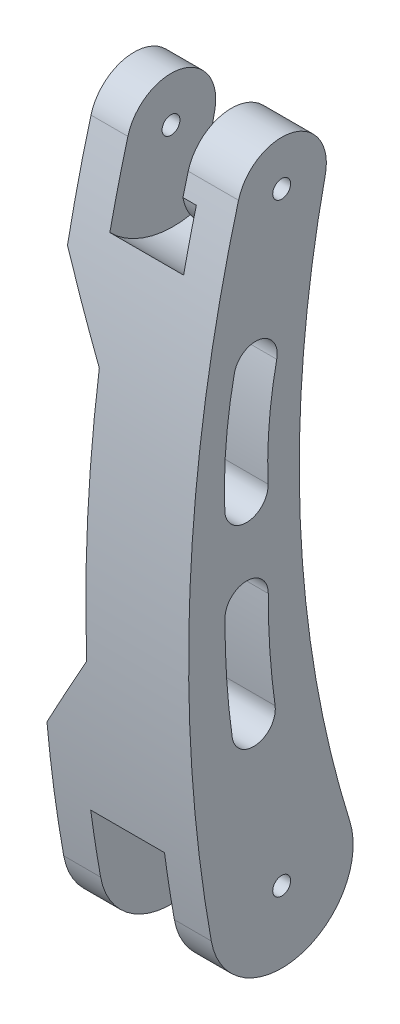
SolidWorks part; units mm, degrees
ref_plane "Plan de face" through (0, 0, 0) normal (0, 0, 1) x (1, 0, 0)
ref_plane "Plan de dessus" through (0, 0, 0) normal (0, 1, 0) x (1, 0, 0)
ref_plane "Plan de droite" through (0, 0, 0) normal (1, 0, 0) x (0, 0, -1)
sketch "Sketch1" plane through (0, 0, 0) normal (1, 0, 0) x (0, 0, -1)
  line L0 (0, 0) -> (0, 31.8922) construction
  line L1 (5.0656, 55.484) -> (-20.7338, 60.769) construction
  line L2 (7.6328, 36.3738) -> (-20.1612, 33.5121) construction
  line L3 (3.9429, 77.8355) -> (-19.7041, 80.4177) construction
  line L4 (4.9513, 101.6614) -> (-16.6278, 105.4128) construction
  arc A0 (-15.7469, -2.8345) -> (15.2745, 4.7632) centre (0, 0) ccw
  arc A1 (9.7669, 132.8534) -> (-9.6513, 137.6176) centre (0, 135) ccw
  circle A2 centre (0, 135) radius 2
  circle A3 centre (0, 0) radius 2
  arc A4 (-15.7469, -2.8345) -> (-9.6513, 137.6176) centre (299.1915, 53.8556) cw
  arc A5 (9.7669, 132.8534) -> (15.2745, 4.7632) centre (253.9392, 79.1889) ccw
  arc A6 (-7.8341, 58.1265) -> (-6.2642, 34.943) centre (152.3595, 57.3292) ccw construction
  arc A11 (-7.8341, 58.1265) -> (-6.2642, 34.943) centre (152.3595, 57.3292) ccw construction
  arc A12 (-12.6754, 58.1506) -> (-11.0581, 34.2664) centre (152.3595, 57.3292) ccw
  arc A13 (-2.9928, 58.1024) -> (-1.4703, 35.6195) centre (152.3595, 57.3292) ccw
  arc A14 (-2.9928, 58.1024) -> (-12.6754, 58.1506) centre (-7.8341, 58.1265) ccw
  arc A15 (-11.0581, 34.2664) -> (-1.4703, 35.6195) centre (-6.2642, 34.943) ccw
  arc A16 (-5.8383, 103.5371) -> (-7.8806, 79.1266) centre (152.311, 78.0144) ccw construction
  arc A17 (-5.8383, 103.5371) -> (-7.8806, 79.1266) centre (90.3799, 83.196) ccw construction
  arc A18 (-10.5749, 104.5385) -> (-12.7179, 78.9263) centre (90.3799, 83.196) ccw
  arc A19 (-1.1016, 102.5357) -> (-3.0434, 79.3269) centre (90.3799, 83.196) ccw
  arc A20 (-1.1016, 102.5357) -> (-10.5749, 104.5385) centre (-5.8383, 103.5371) ccw
  arc A21 (-12.7179, 78.9263) -> (-3.0434, 79.3269) centre (-7.8806, 79.1266) ccw
  point P19 (-7.4701, 46.5062)
  point P33 (-7.6224, 91.3957)
  dimension "D4" = 20
  dimension "D5" = 320
  dimension "D6" = 250
  dimension "D1" = 16
  dimension "D2" = 135
  dimension "D3" = 32
  dimension "D7" = 35.5
extrude "Boss-Extrude1" add sketch "Sketch1" along normal blind 33
ref_plane "Plane1" through (8.25, 0, 0) normal (-1, 0, 0) x (0, 0, 1)
sketch "Sketch2" plane through (8.25, 0, 0) normal (-1, 0, 0) x (0, 0, 1)
  line L3 (0, 135) -> (0, 128.3969) construction
  arc A0 (9.6513, 137.6176) -> (-9.7669, 132.8534) centre (0, 135) ccw construction
  arc A1 (9.6513, 137.6176) -> (-9.7669, 132.8534) centre (0, 135) ccw
  arc A2 (15.7469, -2.8345) -> (9.6513, 137.6176) centre (-299.1915, 53.8556) ccw construction
  arc A3 (-15.2745, 4.7632) -> (-9.7669, 132.8534) centre (-253.9392, 79.1889) ccw construction
  arc A4 (13.6848, 121.0001) -> (9.6513, 137.6176) centre (-299.1915, 53.8556) ccw
  arc A5 (-6.6696, 116.0363) -> (-9.7669, 132.8534) centre (-253.9392, 79.1889) ccw
  arc A6 (13.6848, 121.0001) -> (-6.6696, 116.0363) centre (-0.5289, 135.0702) cw
  dimension "D3" = 20
  dimension "D1" = 17.1
  dimension "D2" = 17.1
extrude "Cut-Extrude1" cut sketch "Sketch2" against normal blind 13.5
sketch "Sketch3" plane through (8.25, 0, 0) normal (-1, 0, 0) x (0, 0, 1)
  line L0 (-3.8062, -15.5407) -> (4.8189, 21.4675) construction
  arc A0 (15.7469, -2.8345) -> (9.6513, 137.6176) centre (-299.1915, 53.8556) ccw construction
  arc A1 (-15.2745, 4.7632) -> (-9.7669, 132.8534) centre (-253.9392, 79.1889) ccw construction
  arc A2 (-15.2745, 4.7632) -> (15.7469, -2.8345) centre (0, 0) ccw construction
  arc A3 (15.7469, -2.8345) -> (17.9617, 11.2666) centre (-299.1915, 53.8556) ccw
  arc A4 (-15.2745, 4.7632) -> (-11.4934, 18.1967) centre (-253.9392, 79.1889) ccw
  arc A5 (-15.2745, 4.7632) -> (15.7469, -2.8345) centre (0, 0) ccw
  arc A6 (-11.4934, 18.1967) -> (17.9617, 11.2666) centre (0.2385, 1.9991) cw
  dimension "D1" = 20
  dimension "D2" = 38
extrude "Cut-Extrude2" cut sketch "Sketch3" against normal blind 16.5
sketch "Sketch4" plane through (0, 0, 0) normal (-1, 0, 0) x (0, 0, 1)
  line L0 (5.5085, 3.4197) -> (6.2141, 16.8837)
  line L1 (1.1904, 17.9515) -> (-3.6413, 5.3646)
  circle A0 centre (0, 0) radius 2
  arc A1 (6.2141, 16.8837) -> (1.1904, 17.9515) centre (3.6177, 17.0198) ccw
  arc A2 (-3.8104, 5.1421) -> (-3.6413, 5.3646) centre (-4.1081, 5.5438) ccw
  arc A3 (-3.8104, 5.1421) -> (5.5725, 3.1477) centre (0, 0) ccw
  arc A4 (5.5085, 3.4197) -> (5.5725, 3.1477) centre (6.0078, 3.3936) ccw
extrude "Cut-Extrude3" cut sketch "Sketch4" against normal blind 5
sketch "Sketch6" plane through (21.75, 0, 0) normal (-1, 0, 0) x (0, 0, 1)
  circle A0 centre (0, 135) radius 2 construction
  arc A1 (-6.6696, 116.0363) -> (13.6848, 121.0001) centre (-0.5289, 135.0702) ccw construction
  arc A2 (-6.6696, 116.0363) -> (-9.7669, 132.8534) centre (-253.9392, 79.1889) ccw construction
  arc A3 (13.6848, 121.0001) -> (9.6513, 137.6176) centre (-299.1915, 53.8556) ccw construction
  arc A4 (-6.6696, 116.0363) -> (-8.8418, 128.4561) centre (-253.9392, 79.1889) ccw
  arc A5 (13.6848, 121.0001) -> (10.8373, 133.1152) centre (-299.1915, 53.8556) ccw
  arc A6 (-8.8418, 128.4561) -> (10.8373, 133.1152) centre (0, 135) ccw
  arc A7 (15.7469, -2.8345) -> (9.6513, 137.6176) centre (-299.1915, 53.8556) ccw construction
  arc A8 (-6.6696, 116.0363) -> (13.6848, 121.0001) centre (-0.5289, 135.0702) ccw
  circle A9 centre (0, 135) radius 2 construction
  dimension "D1" = 11
extrude "Cut-Extrude4" cut sketch "Sketch6" against normal blind 3
sketch "Sketch8" plane through (0, 0, 0) normal (0, 0, 1) x (1, 0, 0)
  line L0 (0, 137.6176) -> (0, -2.8345) construction
  line L1 (0, 115.0001) -> (0, 25)
  line L2 (0, 115.0001) -> (10, 97.6796)
  line L3 (10, 97.6796) -> (10, 42.3205)
  line L4 (10, 42.3205) -> (0, 25)
  line L6 (24.75, 121.0001) -> (8.25, 121.0001) construction
  dimension "D1" = 10
  dimension "D2" = 25
  dimension "D3" = 150
  dimension "D4" = 6
extrude "Cut-Extrude5" cut sketch "Sketch8" against normal through all both and the other way through all
equation "\"Longueur1\"= 135mm"
equation "\"Longueur2\"= 147mm"
equation "\"D2@Sketch1\"=\"Longueur1\""
equation "\"D2@Sketch2\"=\"D1@Sketch2\""
